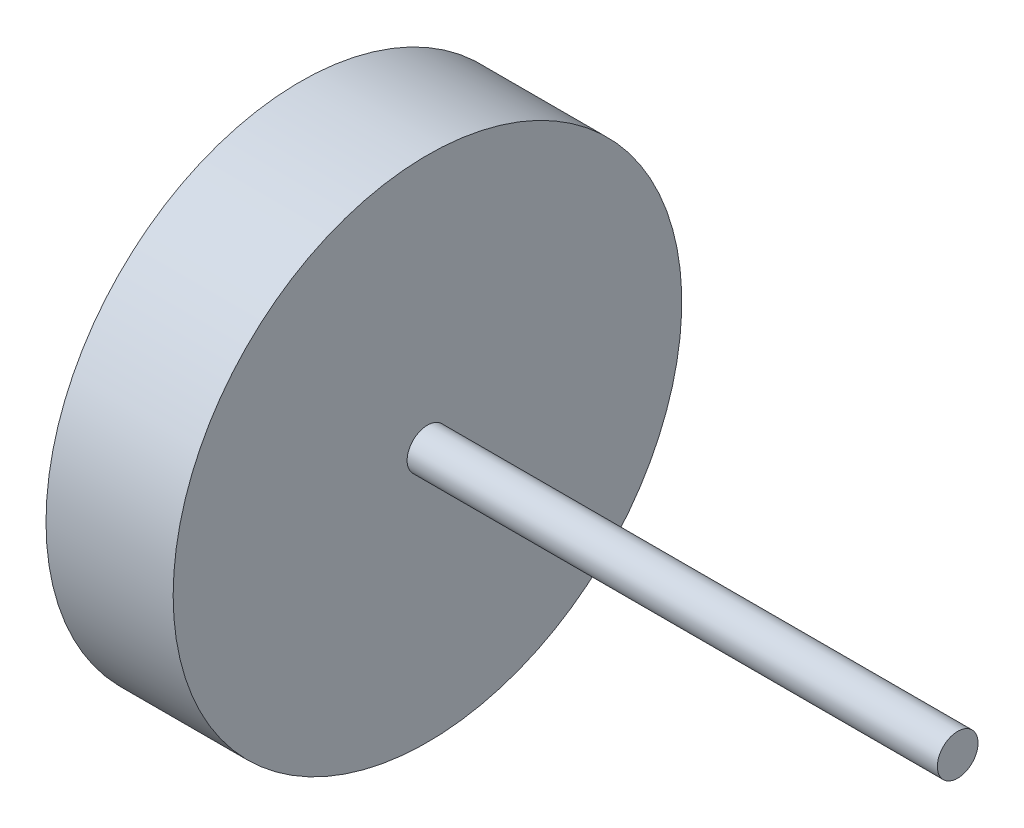
SolidWorks part; units mm, degrees
ref_plane "Front Plane" through (0, 0, 0) normal (0, 0, 1) x (1, 0, 0)
ref_plane "Top Plane" through (0, 0, 0) normal (0, 1, 0) x (1, 0, 0)
ref_plane "Right Plane" through (0, 0, 0) normal (1, 0, 0) x (0, 0, -1)
sketch "Sketch1" plane through (0, 0, 0) normal (0, 1, 0) x (1, 0, 0)
  line L0 (0, 0) -> (0, 252.75) construction
  line L1 (0, 252.75) -> (-140.25, 252.75) construction
  dimension "D1" = 252.75
  dimension "D2" = 140.25
ref_plane "Plane1" through (-140.25, 0, -252.75) normal (-1, 0, 0) x (0, 0, 1)
sketch "Sketch2" plane through (-140.25, 0, -252.75) normal (-1, 0, 0) x (0, 0, 1)
  line L0 (252.75, 0) -> (0, 0) construction
  circle A0 centre (0, 0) radius 50
  point P4 (-11.6307, 0)
  dimension "D1" = 100
extrude "Boss-Extrude1" add sketch "Sketch2" against normal blind 25
sketch "Sketch3" plane through (-140.25, 0, -252.75) normal (-1, 0, 0) x (0, 0, 1)
  circle A1 centre (0, 0) radius 4
  circle A2 centre (0, 0) radius 50 construction
  dimension "D1" = 8
extrude "Boss-Extrude2" add sketch "Sketch3" against normal blind 129.25
